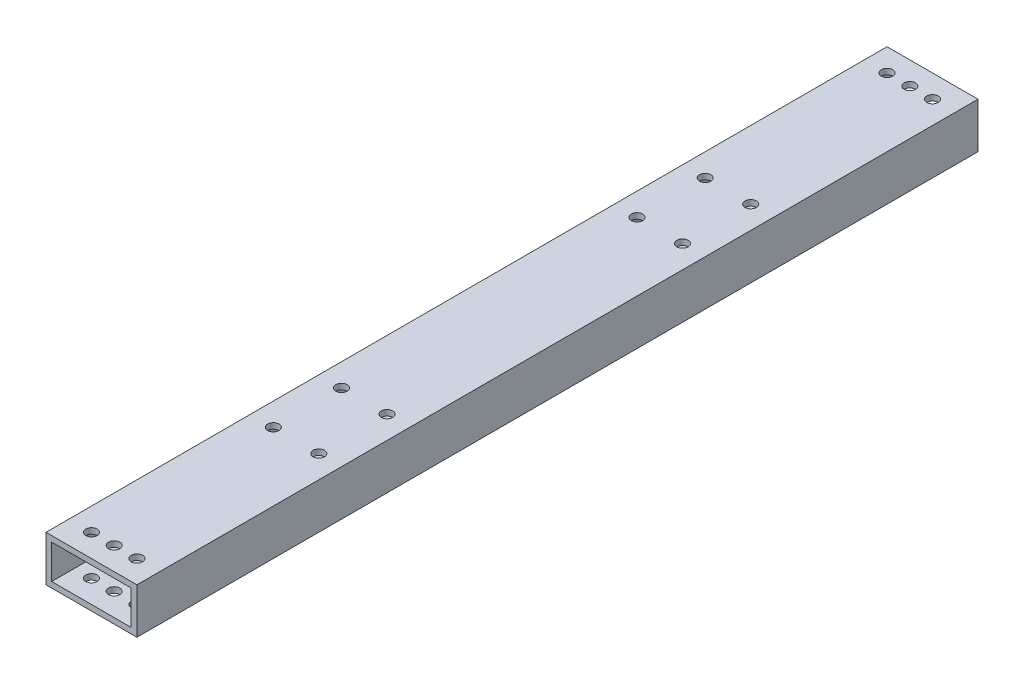
SolidWorks part; units mm, degrees
ref_plane "Front Plane" through (0, 0, 0) normal (0, 0, 1) x (1, 0, 0)
ref_plane "Top Plane" through (0, 0, 0) normal (0, 1, 0) x (1, 0, 0)
ref_plane "Right Plane" through (0, 0, 0) normal (1, 0, 0) x (0, 0, -1)
sketch "Sketch1" plane through (0, 0, 0) normal (0, 0, 1) x (1, 0, 0)
  line L0 (3.175, 22.225) -> (47.625, 22.225)
  line L1 (0, 0) -> (50.8, 0)
  line L2 (0, 0) -> (0, 25.4)
  line L3 (0, 25.4) -> (50.8, 25.4)
  line L4 (50.8, 0) -> (50.8, 25.4)
  line L5 (47.625, 3.175) -> (47.625, 22.225)
  line L6 (3.175, 3.175) -> (47.625, 3.175)
  line L7 (3.175, 3.175) -> (3.175, 22.225)
  dimension "D1" = 25.4
  dimension "D2" = 50.8
  dimension "D3" = 3.175
extrude "Boss-Extrude1" add sketch "Sketch1" along normal blind 469.9
sketch "Sketch3" plane through (0, 25.4, 0) normal (0, 1, 0) x (1, 0, 0)
  line L0 (12.7, -457.2) -> (12.7, -469.9) construction
  line L1 (50.8, -469.9) -> (0, -469.9) construction
  line L2 (12.7, -457.2) -> (0, -457.2) construction
  line L3 (0, -469.9) -> (0, 0) construction
  line L4 (12.7, -12.7) -> (12.7, 0) construction
  line L5 (50.8, 0) -> (0, 0) construction
  line L6 (12.7, -12.7) -> (0, -12.7) construction
  circle A0 centre (12.7, -12.7) radius 3.175
  circle A1 centre (12.7, -457.2) radius 3.175
  circle A2 centre (25.4, -457.2) radius 3.175
  circle A3 centre (25.4, -12.7) radius 3.175
  circle A4 centre (38.1, -457.2) radius 3.175
  circle A5 centre (38.1, -12.7) radius 3.175
  dimension "D2" = 6.35
  dimension "D1" = 12.7
  dimension "D3" = 12.7
extrude "Cut-Extrude1" cut sketch "Sketch3" against normal through all both
sketch "Sketch4" plane through (0, 25.4, 0) normal (0, 1, 0) x (1, 0, 0)
  line L0 (0, -234.95) -> (12.7, -234.95) construction
  line L1 (0, -469.9) -> (0, 0) construction
  line L2 (12.7, -234.95) -> (12.7, -152.4) construction
  line L3 (12.7, -234.95) -> (12.7, -317.5) construction
  line L4 (12.7, -152.4) -> (12.7, -114.3) construction
  line L5 (12.7, -317.5) -> (12.7, -355.6) construction
  line L6 (25.4, 0) -> (25.4, -469.9) construction
  line L7 (50.8, 0) -> (0, 0) construction
  line L8 (50.8, -469.9) -> (0, -469.9) construction
  circle A1 centre (12.7, -152.4) radius 3.175
  circle A2 centre (12.7, -317.5) radius 3.175
  circle A3 centre (12.7, -114.3) radius 3.175
  circle A4 centre (12.7, -355.6) radius 3.175
  circle A5 centre (38.1, -114.3) radius 3.175
  circle A6 centre (38.1, -152.4) radius 3.175
  circle A7 centre (38.1, -317.5) radius 3.175
  circle A8 centre (38.1, -355.6) radius 3.175
  dimension "D2" = 82.55
  dimension "D3" = 6.35
  dimension "D1" = 12.7
  dimension "D4" = 38.1
extrude "Cut-Extrude2" cut sketch "Sketch4" against normal through all both and the other way through all
